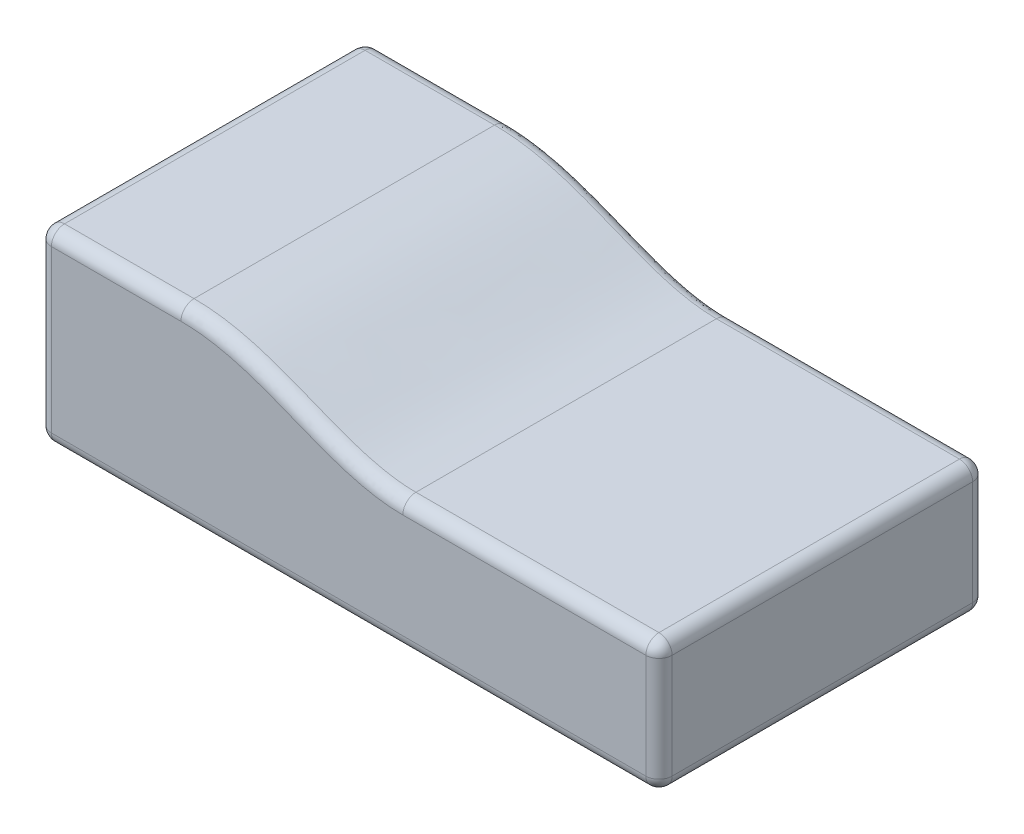
SolidWorks part; units mm, degrees
ref_plane "Front Plane" through (0, 0, 0) normal (0, 0, 1) x (1, 0, 0)
ref_plane "Top Plane" through (0, 0, 0) normal (0, 1, 0) x (1, 0, 0)
ref_plane "Right Plane" through (0, 0, 0) normal (1, 0, 0) x (0, 0, -1)
sketch "Sketch2" plane through (0, 0, 0) normal (0, 1, 0) x (1, 0, 0)
  line L1 (23.65, -12.45) -> (-23.65, -12.45)
  line L2 (23.65, -12.45) -> (23.65, 12.45)
  line L3 (23.65, 12.45) -> (-23.65, 12.45)
  line L4 (-23.65, -12.45) -> (-23.65, 12.45)
  line L5 (23.65, -12.45) -> (-23.65, 12.45) construction
  line L6 (23.65, 12.45) -> (-23.65, -12.45) construction
  point P0 (0, 0)
  dimension "D1" = 24.9
  dimension "D2" = 47.3
extrude "Boss-Extrude1" add sketch "Sketch2" against normal blind 14.3
sketch "Sketch3" plane through (0, 0, -12.45) normal (0, 0, -1) x (-1, 0, 0)
  line L0 (-23.65, -4.3263) -> (-4.1283, -4.3263)
  line L1 (-23.65, -14.3) -> (-23.65, 0) construction
  line L2 (-23.65, 0) -> (23.65, 0) construction
  line L3 (18.4612, 0) -> (7.0976, 0) construction
  line L4 (3.3022, -4.3263) -> (-5.0196, -4.3263) construction
  line L5 (-23.65, -4.3263) -> (-23.65, 0)
  line L6 (-23.65, 0) -> (12.7794, 0)
  spline S0 degree 3 poles (-4.1283, -4.3263) (1.4862, -4.3263) (6.2589, 0) (12.7794, 0) knots 0 0 0 0 1 1 1 1
extrude "Cut-Extrude1" cut sketch "Sketch3" against normal through all both and the other way through all
fillet "Fillet1" radius 1 16 edges at (-23.65, -14.3, 0) (-23.65, 0, 0) (-23.65, -7.15, -12.45) (0, -14.3, -12.45) (13.8891, -4.3263, -12.45) (23.65, -9.3131, -12.45) (23.65, -14.3, 0) (23.65, -4.3263, 0) (13.8891, -4.3263, 12.45) (23.65, -9.3131, 12.45) (0, -14.3, 12.45) (-23.65, -7.15, 12.45) (-18.2147, 0, 12.45)
